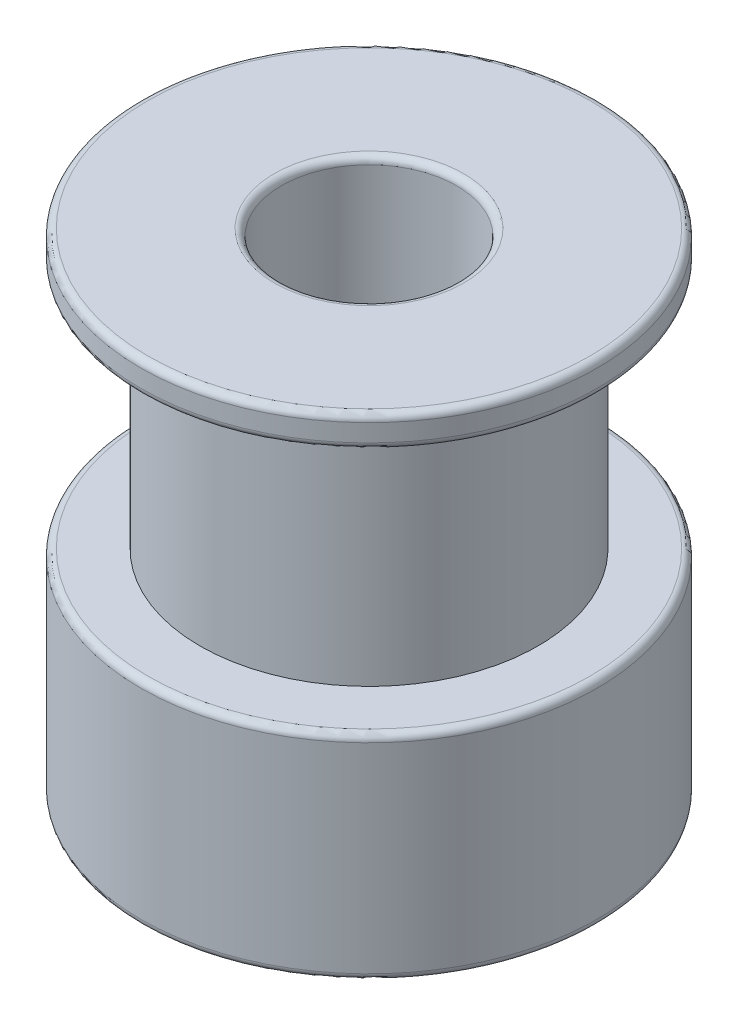
SolidWorks part; units mm, degrees
ref_plane "Front Plane" through (0, 0, 0) normal (0, 0, 1) x (1, 0, 0)
ref_plane "Top Plane" through (0, 0, 0) normal (0, 1, 0) x (1, 0, 0)
ref_plane "Right Plane" through (0, 0, 0) normal (1, 0, 0) x (0, 0, -1)
sketch "Sketch1" plane through (0, 0, 0) normal (0, 1, 0) x (1, 0, 0)
  circle A0 centre (0, 0) radius 6.5
  circle A1 centre (0, 0) radius 2.5
  dimension "D1" = 5
  dimension "D2" = 13
extrude "Boss-Extrude1" add sketch "Sketch1" along normal blind 14
sketch "Sketch2" plane through (0, 0, 0) normal (0, 0, 1) x (1, 0, 0)
  circle A0 centre (0, 3) radius 1.25
  dimension "D1" = 2.5
  dimension "D2" = 3
extrude "Cut-Extrude1" cut sketch "Sketch2" against normal up to next
sketch "Sketch3" plane through (0, 14, 0) normal (0, 1, 0) x (1, 0, 0)
  circle A0 centre (0, 0) radius 4.815
  circle A1 centre (0, 0) radius 6.5 construction
  circle A2 centre (0, 0) radius 6.5
  dimension "D1" = 9.63
extrude "Cut-Extrude2" cut sketch "Sketch3" against normal blind 7 from offset 0.9 offset against normal yes
sketch "Sketch4" plane through (0, 0, 0) normal (1, 0, 0) x (0, 0, -1)
  circle A0 centre (0, 3) radius 1.25
  dimension "D1" = 2.5
  dimension "D2" = 3
extrude "Cut-Extrude3" cut sketch "Sketch4" against normal up to next contours A0
fillet "Fillet1" radius 0.2 7 edges at (0, 13.1, 6.5) (0, 14, 6.5) (0, 6.1, 6.5) (0, 0, 6.5) (-1.2223, 3.2619, -6.384) (0, 14, 2.5) (-6.384, 3.2619, 1.2223)
ref_plane "Plane1" through (0, 9.6, 0) normal (0, -1, 0) x (-1, 0, 0)
